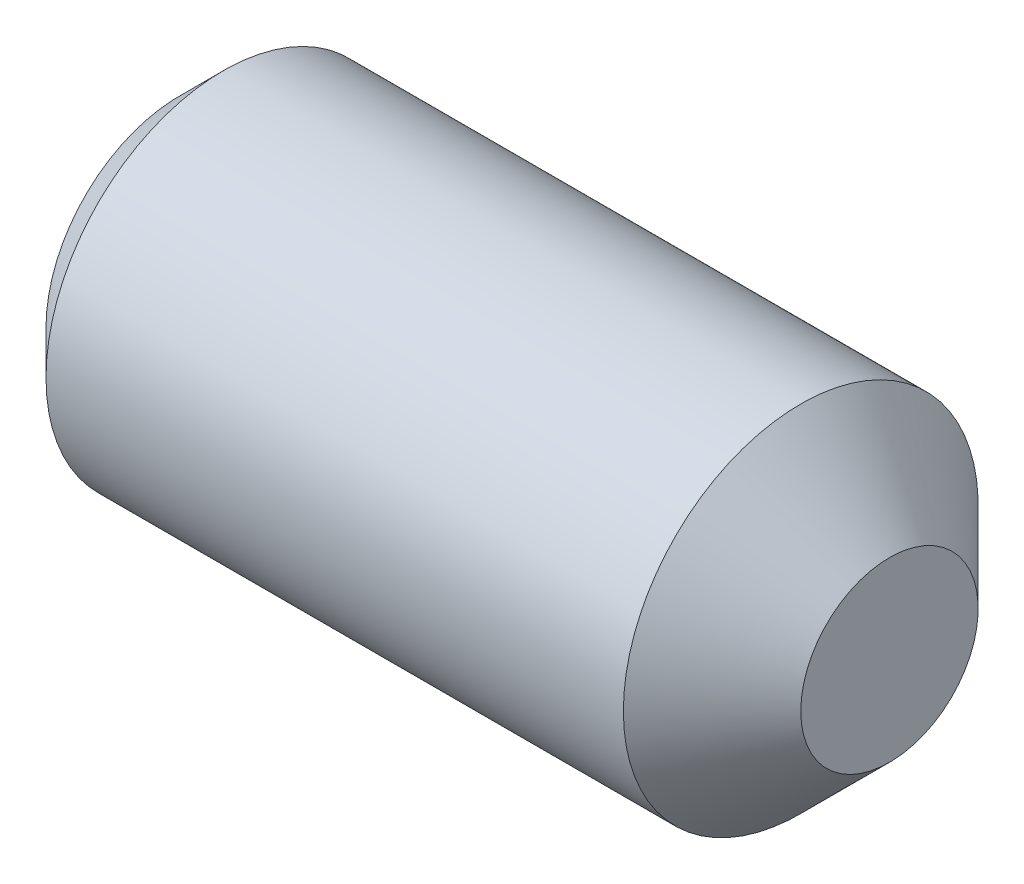
SolidWorks part; units mm, degrees
ref_plane "Front Plane" through (0, 0, 0) normal (0, 0, 1) x (1, 0, 0)
ref_plane "Top Plane" through (0, 0, 0) normal (0, 1, 0) x (1, 0, 0)
ref_plane "Right Plane" through (0, 0, 0) normal (1, 0, 0) x (0, 0, -1)
ref_plane "Plane1" through (0, 0, 0) normal (0, 0, 1) x (1, 0, 0)
sketch "Sketch1" plane through (0, 0, 0) normal (0, 0, 1) x (1, 0, 0)
  line L0 (-4, 0) -> (-4, 0.7545)
  line L1 (-4, 0.7545) -> (-3.7545, 1)
  line L2 (-3.7545, 1) -> (-0.5, 1)
  line L3 (-0.5, 1) -> (0, 0.5)
  line L4 (0, 0.5) -> (0, 0)
  line L5 (0, 0) -> (-4, 0)
  line L6 (0, 0) -> (-4, 0) construction
revolve "Revolve1" add sketch "Sketch1" angle 360 about L6
ref_plane "Plane2" through (-4, 0, 0) normal (-1, 0, 0) x (0, 0, 1)
sketch "Sketch2" plane through (-4, 0, 0) normal (-1, 0, 0) x (0, 0, 1)
  line L0 (-0.2598, -0.45) -> (0.2598, -0.45)
  line L1 (0.2598, -0.45) -> (0.5196, 0)
  line L2 (0.5196, 0) -> (0.2598, 0.45)
  line L3 (0.2598, 0.45) -> (-0.2598, 0.45)
  line L4 (-0.2598, 0.45) -> (-0.5196, 0)
  line L5 (-0.5196, 0) -> (-0.2598, -0.45)
extrude "Cut-Extrude1" cut sketch "Sketch2" against normal blind 0.8
ref_plane "Plane3" through (0, 0, 0) normal (0, 0, 1) x (1, 0, 0)
sketch "Sketch3" plane through (0, 0, 0) normal (0, 0, 1) x (1, 0, 0)
  line L0 (-3.2, 0) -> (-3.2, 0.45)
  line L1 (-3.2, 0.45) -> (-2.9402, 0)
  line L2 (-2.9402, 0) -> (-3.2, 0)
  line L3 (-2.9402, 0) -> (-3.2, 0) construction
revolve "Cut-Revolve1" cut sketch "Sketch3" angle 360 about L3
